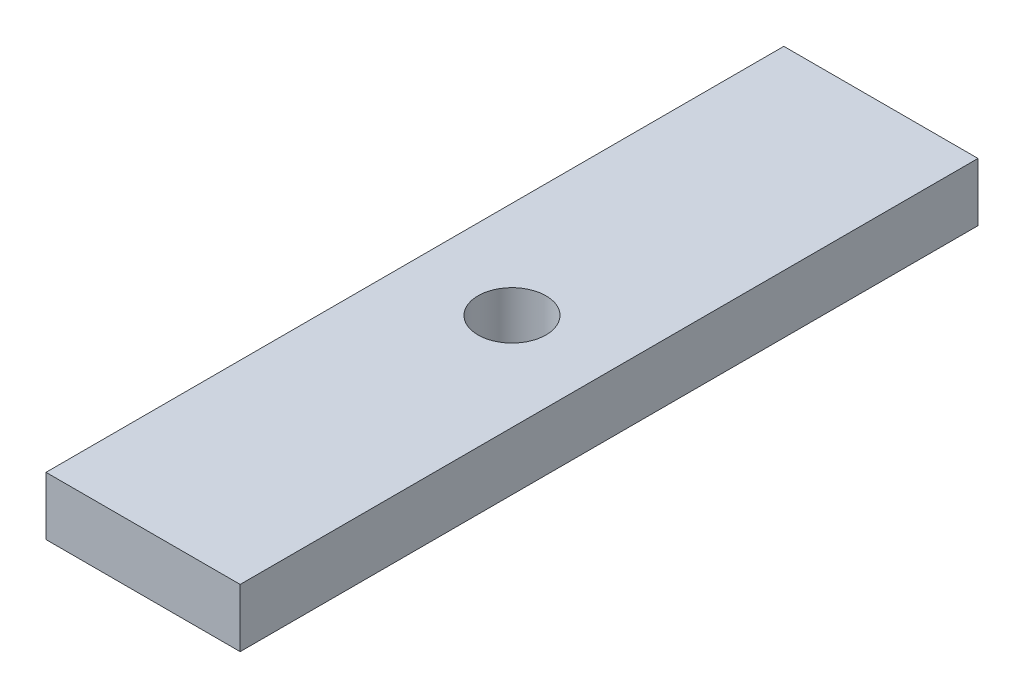
SolidWorks part; units mm, degrees
ref_plane "Front Plane" through (0, 0, 0) normal (0, 0, 1) x (1, 0, 0)
ref_plane "Top Plane" through (0, 0, 0) normal (0, 1, 0) x (1, 0, 0)
ref_plane "Right Plane" through (0, 0, 0) normal (1, 0, 0) x (0, 0, -1)
sketch "Sketch1" plane through (0, 0, 0) normal (1, 0, 0) x (0, 0, -1)
  line L1 (0, 0) -> (-38, 0)
  line L2 (0, 0) -> (0, 3)
  line L3 (0, 3) -> (-38, 3)
  line L4 (-38, 0) -> (-38, 3)
  dimension "D1" = 38
  dimension "D2" = 3
extrude "Boss-Extrude2" add sketch "Sketch1" along normal blind 10
sketch "Sketch2" plane through (0, 3, 0) normal (0, 1, 0) x (1, 0, 0)
  line L0 (5, 0) -> (5, -38) construction
  line L1 (10, 0) -> (0, 0) construction
  line L2 (10, -38) -> (0, -38) construction
  circle A0 centre (5, -19) radius 1.75
  dimension "D1" = 3.5
extrude "Cut-Extrude1" cut sketch "Sketch2" against normal blind 10
